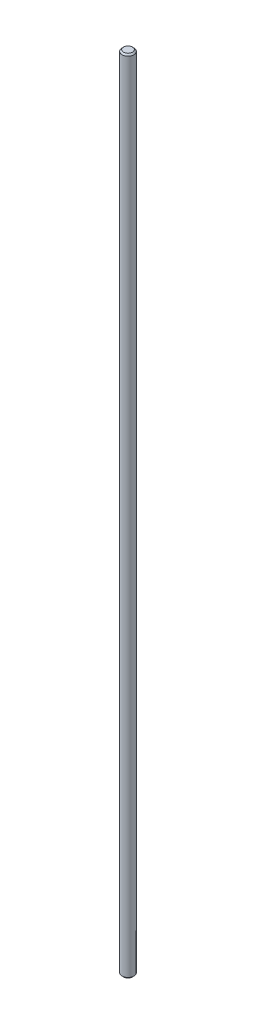
SolidWorks part; units mm, degrees
ref_plane "前视基准面" through (0, 0, 0) normal (0, 0, 1) x (1, 0, 0)
ref_plane "上视基准面" through (0, 0, 0) normal (0, 1, 0) x (1, 0, 0)
ref_plane "右视基准面" through (0, 0, 0) normal (1, 0, 0) x (0, 0, -1)
sketch "草图1" plane through (0, 0, 0) normal (0, 1, 0) x (1, 0, 0)
  circle A0 centre (0, 0) radius 2
  dimension "D1" = 4
extrude "凸台-拉伸1" add sketch "草图1" along normal mid plane 270
chamfer "倒角1" distance 0.5 angle 45 2 edges at (0, -135, 2) (0, 135, 2)
